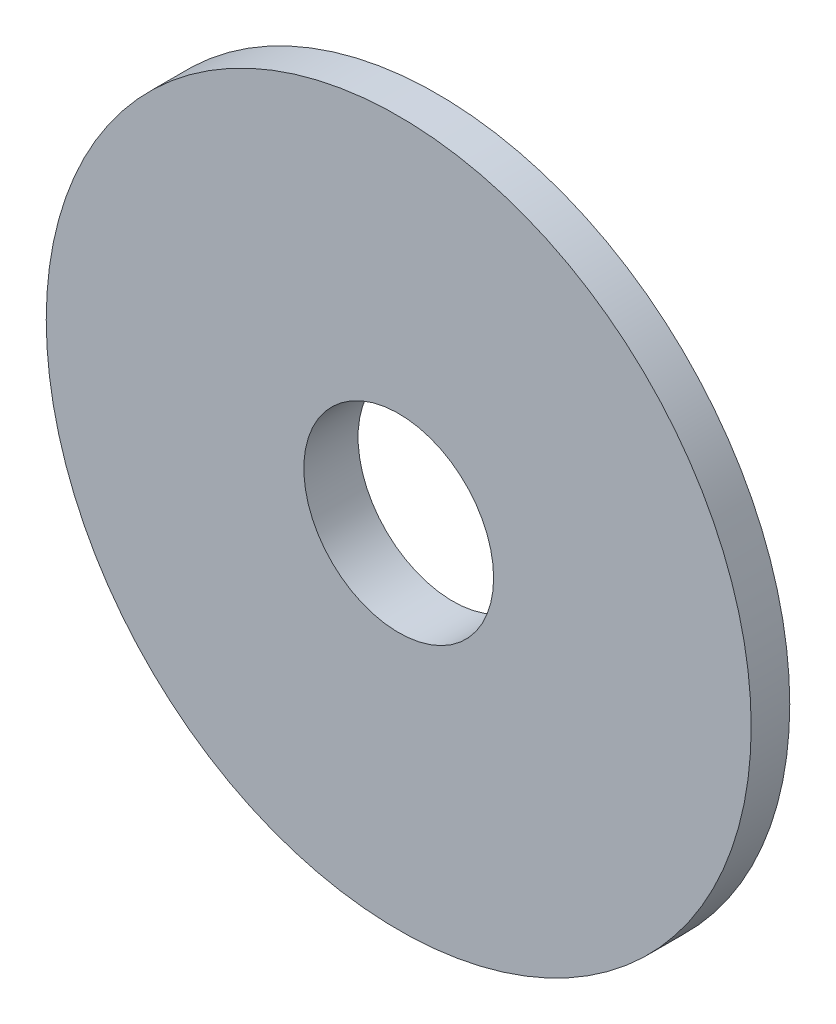
SolidWorks part; units mm, degrees
ref_plane "Front Plane" through (0, 0, 0) normal (0, 0, 1) x (1, 0, 0)
ref_plane "Top Plane" through (0, 0, 0) normal (0, 1, 0) x (1, 0, 0)
ref_plane "Right Plane" through (0, 0, 0) normal (1, 0, 0) x (0, 0, -1)
sketch "Sketch1" plane through (0, 0, 0) normal (0, 0, 1) x (1, 0, 0)
  circle A0 centre (0, 0) radius 3.5
  circle A1 centre (0, 0) radius 13
extrude "Boss-Extrude1" add sketch "Sketch1" along normal blind 2
chamfer "Chamfer1" distance 1 angle 30 1 edges at (13, 0, 0)
